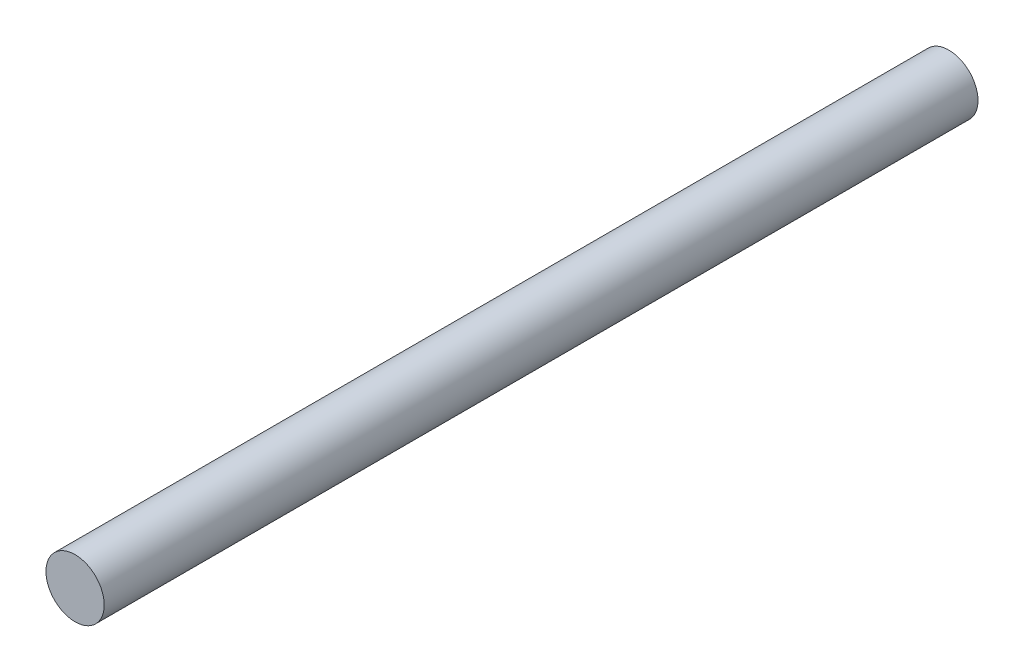
SolidWorks part; units mm, degrees
material "LW-PLA"
ref_plane "Front Plane" through (0, 0, 0) normal (0, 0, 1) x (1, 0, 0)
ref_plane "Top Plane" through (0, 0, 0) normal (0, 1, 0) x (1, 0, 0)
ref_plane "Right Plane" through (0, 0, 0) normal (1, 0, 0) x (0, 0, -1)
sketch "Sketch1" plane through (0, 0, 0) normal (0, 0, 1) x (1, 0, 0)
  circle A0 centre (0, 0) radius 0.5
  dimension "D1" = 1
extrude "Boss-Extrude1" add sketch "Sketch1" along normal blind 15
